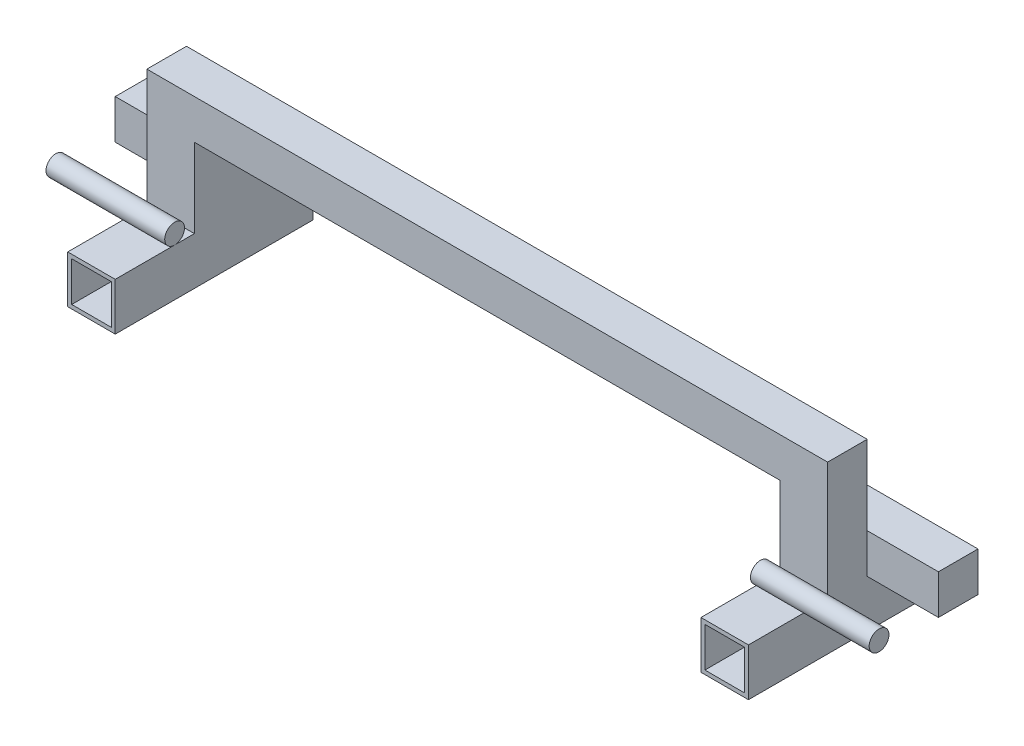
SolidWorks part; units mm, degrees
ref_plane "Front Plane" through (0, 0, 0) normal (0, 0, 1) x (1, 0, 0)
ref_plane "Top Plane" through (0, 0, 0) normal (0, 1, 0) x (1, 0, 0)
ref_plane "Right Plane" through (0, 0, 0) normal (1, 0, 0) x (0, 0, -1)
sketch "Sketch1" plane through (0, 0, 0) normal (0, 0, 1) x (1, 0, 0)
  line L0 (-114.7545, 24.3796) -> (-102.7545, 24.3796)
  line L1 (-113.7545, 13.3796) -> (-103.7545, 13.3796)
  line L2 (-113.7545, 13.3796) -> (-113.7545, 23.3796)
  line L3 (-113.7545, 23.3796) -> (-103.7545, 23.3796)
  line L4 (-103.7545, 13.3796) -> (-103.7545, 23.3796)
  line L9 (-102.7545, 12.3796) -> (-102.7545, 24.3796)
  line L10 (-114.7545, 12.3796) -> (-102.7545, 12.3796)
  line L11 (-114.7545, 12.3796) -> (-114.7545, 24.3796)
  dimension "D1" = 10
  dimension "D2" = 10
  dimension "D5" = 1
extrude "Boss-Extrude1" add sketch "Sketch1" along normal blind 50
ref_plane "Plane1" through (-28.7545, 0, 0) normal (-1, 0, 0) x (0, 0, 1)
sketch "Sketch2" plane through (-102.7545, 0, 0) normal (1, 0, 0) x (0, 0, -1)
  line L2 (-50, 24.3796) -> (0, 24.3796) construction
  line L3 (-20, 24.3796) -> (-10, 24.3796)
  line L4 (-20, 24.3796) -> (-20, 34.3796)
  line L5 (-20, 34.3796) -> (-10, 34.3796)
  line L6 (-10, 24.3796) -> (-10, 34.3796)
  line L7 (-50, 12.3796) -> (-50, 24.3796) construction
  circle A0 centre (-35, 26.8796) radius 2.5
  line M2 (0, 24.3796) -> (-50, 24.3796)
  dimension "D1" = 15
  dimension "D5" = 2.5
  dimension "D2" = 5
  dimension "D3" = 10
  dimension "D4" = 10
extrude "Boss-Extrude2" add sketch "Sketch2" against normal blind 30 contours L6 L5 L4 M2 | A0
sketch "Sketch3" plane through (0, 24.3796, 0) normal (0, 1, 0) x (1, 0, 0)
  line L0 (-102.7545, -50) -> (-102.7545, -20) construction
  line L1 (-114.7545, -20) -> (-102.7545, -20)
  line L2 (-114.7545, -20) -> (-114.7545, -30)
  line L3 (-114.7545, -30) -> (-102.7545, -30)
  line L4 (-102.7545, -20) -> (-102.7545, -30)
  dimension "D1" = 10
extrude "Boss-Extrude3" add sketch "Sketch3" along normal blind 20 contours L1 L4 L3 L2
mirror "Mirror6" about plane through (-28.7545, 0, 0) normal (-1, 0, 0) of bodies 109 104
sketch "Sketch5" plane through (-114.7545, 0, 0) normal (-1, 0, 0) x (0, 0, 1)
  line L1 (20, 44.3796) -> (30, 44.3796)
  line L2 (20, 44.3796) -> (20, 54.3796)
  line L3 (20, 54.3796) -> (30, 54.3796)
  line L4 (30, 44.3796) -> (30, 54.3796)
  dimension "D1" = 10
  dimension "D2" = 10
extrude "Boss-Extrude4" add sketch "Sketch5" against normal up to vertex contours L3 L4 L1 L2
